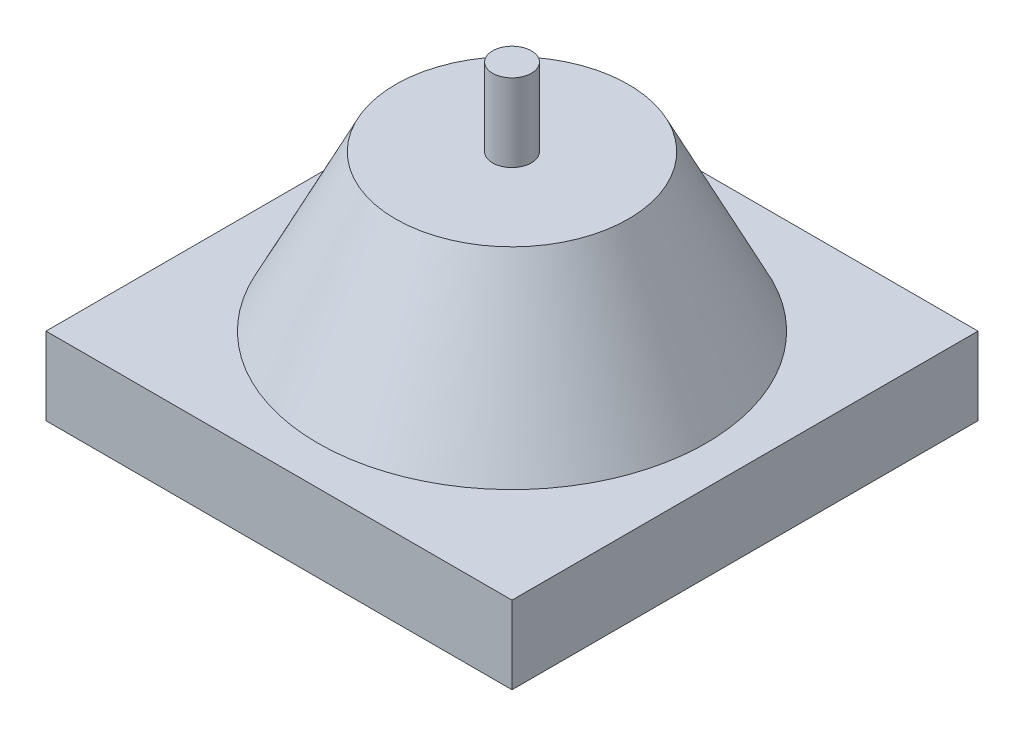
SolidWorks part; units mm, degrees
ref_plane "Front Plane" through (0, 0, 0) normal (0, 0, 1) x (1, 0, 0)
ref_plane "Top Plane" through (0, 0, 0) normal (0, 1, 0) x (1, 0, 0)
ref_plane "Right Plane" through (0, 0, 0) normal (1, 0, 0) x (0, 0, -1)
sketch "Sketch3" plane through (0, 0, 0) normal (0, 1, 0) x (1, 0, 0)
  circle A0 centre (0, 0) radius 63.5
  dimension "D1" = 127
sketch "Sketch4" plane through (0, 0, 0) normal (0, 0, 1) x (1, 0, 0)
  line L0 (0, 0) -> (0, 50.8)
  line L1 (63.5, 0) -> (-63.5, 0) construction
  dimension "D1" = 50.8
ref_plane "Plane1" through (0, 50.8, 0) normal (0, 1, 0) x (1, 0, 0)
sketch "Sketch5" plane through (0, 50.8, 0) normal (0, 1, 0) x (1, 0, 0)
  circle A0 centre (0, 0) radius 38.1
  dimension "D1" = 76.2
loft "Loft1" add profiles "Sketch3", "Sketch5"
sketch "Sketch6" plane through (0, 0, 0) normal (0, -1, 0) x (1, 0, 0)
  line L1 (-76.2, -76.2) -> (76.2, -76.2)
  line L2 (-76.2, -76.2) -> (-76.2, 76.2)
  line L3 (-76.2, 76.2) -> (76.2, 76.2)
  line L4 (76.2, -76.2) -> (76.2, 76.2)
  line L5 (-76.2, -76.2) -> (76.2, 76.2) construction
  line L6 (-76.2, 76.2) -> (76.2, -76.2) construction
  point P0 (0, 0)
  dimension "D1" = 152.4
  dimension "D2" = 152.4
extrude "Boss-Extrude1" add sketch "Sketch6" along normal blind 25.4
sketch "Sketch7" plane through (0, 50.8, 0) normal (0, 1, 0) x (1, 0, 0)
  circle A0 centre (0, 0) radius 6.35
  dimension "D1" = 12.7
extrude "Boss-Extrude2" add sketch "Sketch7" along normal blind 25.4
